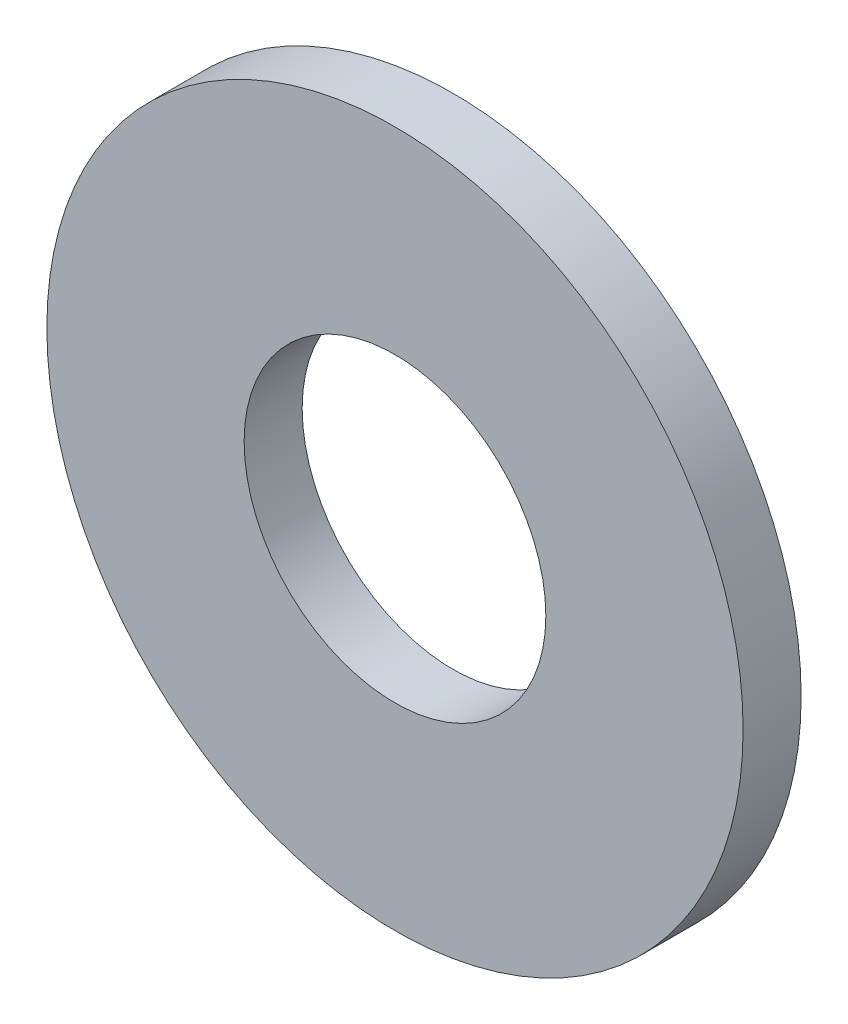
SolidWorks part; units mm, degrees
ref_plane "Front Plane" through (0, 0, 0) normal (0, 0, 1) x (1, 0, 0)
ref_plane "Top Plane" through (0, 0, 0) normal (0, 1, 0) x (1, 0, 0)
ref_plane "Right Plane" through (0, 0, 0) normal (1, 0, 0) x (0, 0, -1)
sketch "Sketch1" plane through (0, 0, 0) normal (0, 0, 1) x (1, 0, 0)
  circle A0 centre (0, 0) radius 6
  circle A1 centre (0, 0) radius 2.6
  dimension "D1" = 12
  dimension "D2" = 5.2
extrude "Boss-Extrude1" add sketch "Sketch1" along normal blind 1
